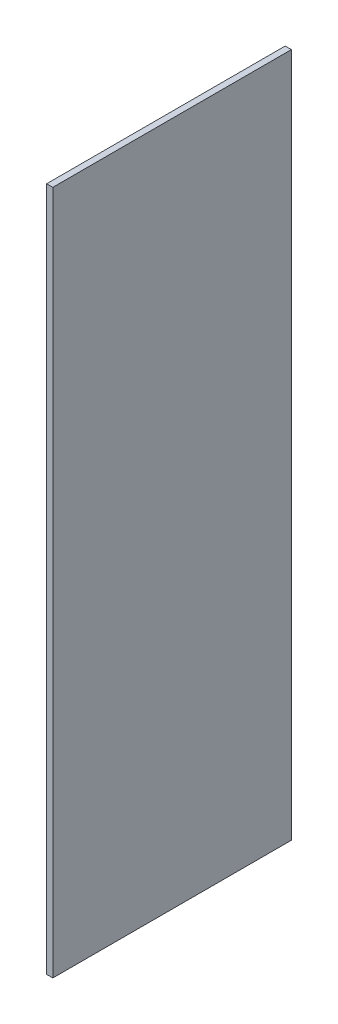
SolidWorks part; units mm, degrees
ref_plane "Front Plane" through (0, 0, 0) normal (0, 0, 1) x (1, 0, 0)
ref_plane "Top Plane" through (0, 0, 0) normal (0, 1, 0) x (1, 0, 0)
ref_plane "Right Plane" through (0, 0, 0) normal (1, 0, 0) x (0, 0, -1)
sketch "Sketch1" plane through (0, 0, 0) normal (1, 0, 0) x (0, 0, -1)
  line L1 (0, 0) -> (154, 0)
  line L2 (0, 0) -> (0, 442)
  line L3 (0, 442) -> (154, 442)
  line L4 (154, 0) -> (154, 442)
  dimension "D1" = 442
  dimension "D2" = 154
extrude "Boss-Extrude1" add sketch "Sketch1" along normal blind 4
